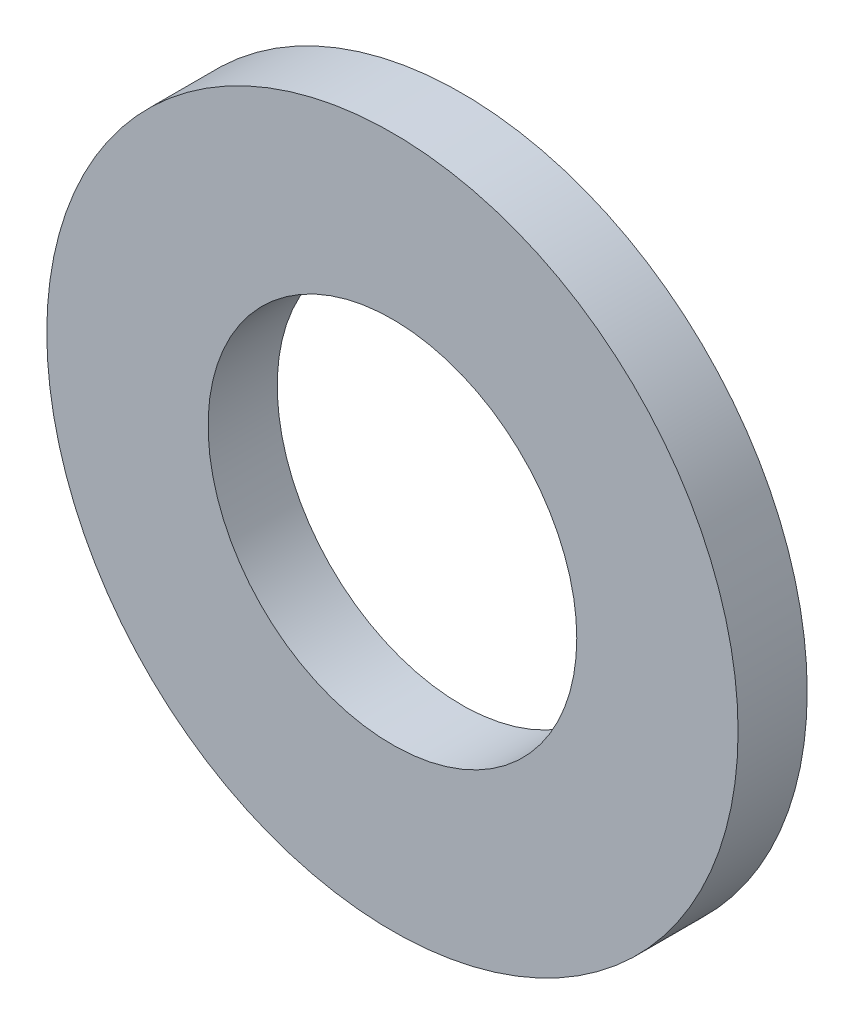
SolidWorks part; units mm, degrees
material "Acier non allié"
ref_plane "Plan de face" through (0, 0, 0) normal (0, 0, 1) x (1, 0, 0)
ref_plane "Plan de dessus" through (0, 0, 0) normal (0, 1, 0) x (1, 0, 0)
ref_plane "Plan de droite" through (0, 0, 0) normal (1, 0, 0) x (0, 0, -1)
sketch "Esquisse1" plane through (0, 0, 0) normal (0, 0, 1) x (1, 0, 0)
  circle A0 centre (0, 0) radius 3.2
  circle A1 centre (0, 0) radius 6
  dimension "D1" = 12
  dimension "D2" = 6.4
extrude "Boss.-Extru.1" add sketch "Esquisse1" along normal blind 1.2
